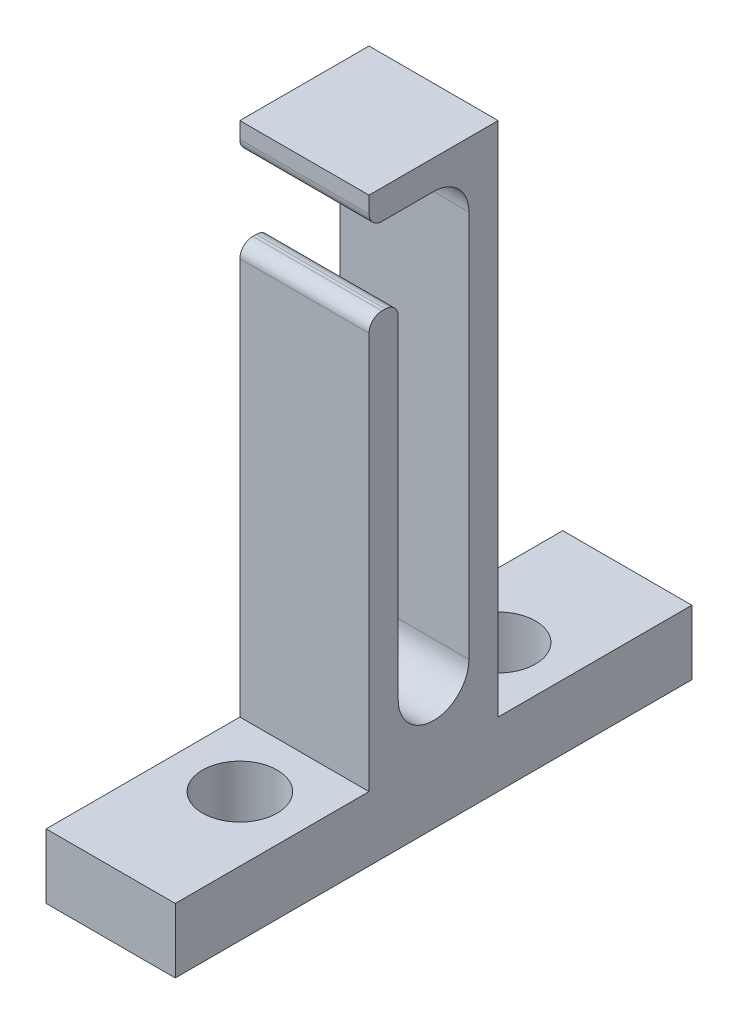
SolidWorks part; units mm, degrees
ref_plane "Front Plane" through (0, 0, 0) normal (0, 0, 1) x (1, 0, 0)
ref_plane "Top Plane" through (0, 0, 0) normal (0, 1, 0) x (1, 0, 0)
ref_plane "Right Plane" through (0, 0, 0) normal (1, 0, 0) x (0, 0, -1)
sketch "Sketch1" plane through (0, 0, 0) normal (0, 0, 1) x (1, 0, 0)
  line L1 (-6.35, -25.4) -> (6.35, -25.4)
  line L2 (-6.35, -25.4) -> (-6.35, 25.4)
  line L3 (-6.35, 25.4) -> (6.35, 25.4)
  line L4 (6.35, -25.4) -> (6.35, 25.4)
  line L5 (-6.35, -25.4) -> (6.35, 25.4) construction
  line L6 (-6.35, 25.4) -> (6.35, -25.4) construction
  point P0 (0, 0)
  dimension "D1" = 50.8
  dimension "D2" = 12.7
extrude "Boss-Extrude1" add sketch "Sketch1" along normal blind 12.7
sketch "Sketch2" plane through (6.35, 0, 0) normal (1, 0, 0) x (0, 0, -1)
  line L0 (-6.35, 19.05) -> (-6.35, -19.05) construction
  line L1 (-2.875, 19.05) -> (-2.875, -19.05)
  line L3 (-12.7, 25.4) -> (0, 25.4) construction
  line L4 (-9.825, 22.525) -> (-12.7, 22.525)
  line L5 (-12.7, -25.4) -> (-12.7, 25.4) construction
  line L6 (-12.7, 22.525) -> (-12.7, 14.905)
  line L7 (-12.7, 14.905) -> (-9.825, 14.905)
  line L8 (-9.825, 14.905) -> (-9.825, -19.05)
  line L9 (-12.7, -25.4) -> (0, -25.4) construction
  line L10 (-9.825, 22.525) -> (-6.35, 22.525)
  arc A0 (-2.875, 19.05) -> (-6.35, 22.525) centre (-6.35, 19.05) ccw
  arc A1 (-9.825, -19.05) -> (-2.875, -19.05) centre (-6.35, -19.05) ccw
  point P2 (-6.35, 0)
  point P5 (0, 0)
  point P12 (-6.35, 25.4)
  point P15 (-3.1953, 18.6914)
  point P25 (-6.35, 0)
  dimension "D1" = 3.475
  dimension "D2" = 6.35
  dimension "D3" = 7.62
extrude "Cut-Extrude1" cut sketch "Sketch2" against normal through all
fillet "Fillet1" radius 1.27 3 edges at (0, 14.905, 12.7) (0, 14.905, 9.825) (0, 22.525, 12.7)
sketch "Sketch3" plane through (0, -25.4, 0) normal (0, -1, 0) x (1, 0, 0)
  line L1 (-6.35, -19.05) -> (6.35, -19.05)
  line L2 (-6.35, -19.05) -> (-6.35, 31.75)
  line L3 (-6.35, 31.75) -> (6.35, 31.75)
  line L4 (6.35, -19.05) -> (6.35, 31.75)
  line L5 (-6.35, -19.05) -> (6.35, 31.75) construction
  line L6 (-6.35, 31.75) -> (6.35, -19.05) construction
  line L8 (0, 31.75) -> (0, 0) construction
  line L9 (6.35, 6.35) -> (-6.35, 6.35) construction
  line L11 (-6.35, 12.7) -> (-6.35, 0) construction
  circle A0 centre (0, -6.35) radius 3.675
  circle A1 centre (0, 19.05) radius 3.675
  point P0 (0, 6.35)
  point P5 (-9.1714, 6.35)
  point P6 (0, 17.8244)
  point P7 (-6.35, 28.7938)
  point P8 (0, 6.6862)
  point P18 (-6.35, 6.35)
  dimension "D2" = 7.35
  dimension "D1" = 12.7
  dimension "D3" = 25.4
  dimension "D4" = 50.8
extrude "Boss-Extrude2" add sketch "Sketch3" along normal blind 6.35
equation "\"D1@Sketch2\"=0.125in + 0.3mm"
